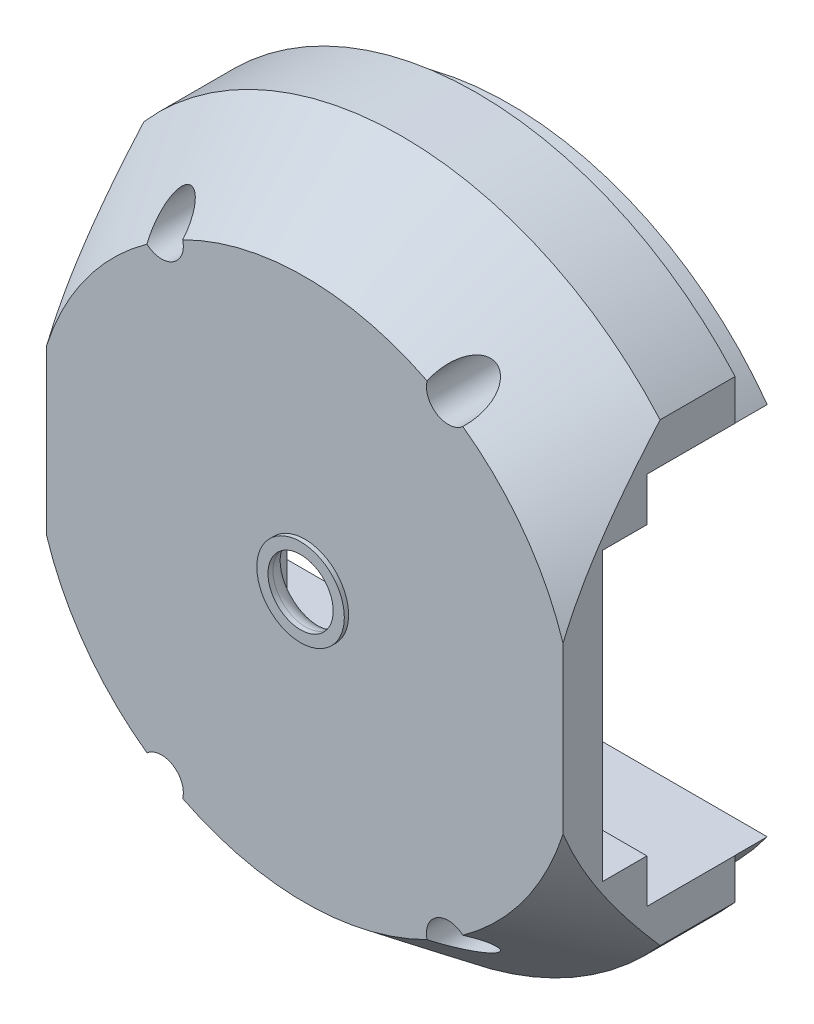
SolidWorks part; units mm, degrees
ref_plane "Front Plane" through (0, 0, 0) normal (0, 0, 1) x (1, 0, 0)
ref_plane "Top Plane" through (0, 0, 0) normal (0, 1, 0) x (1, 0, 0)
ref_plane "Right Plane" through (0, 0, 0) normal (1, 0, 0) x (0, 0, -1)
sketch "Sketch1" plane through (0, 0, 0) normal (0, 0, 1) x (1, 0, 0)
  line L1 (-18.8872, 0) -> (15.5738, 0) construction
  arc A0 (-22.225, -0.0261) -> (22.225, 0) centre (0, 0) ccw
  arc A1 (-22.225, -0.0261) -> (22.225, 0) centre (0, 0) cw
  dimension "D1" = 44.45
extrude "Extrude1" add sketch "Sketch1" along normal blind 2.25
sketch "Sketch2" plane through (0, 0, 2.25) normal (0, 0, 1) x (1, 0, 0)
  line L1 (-19.1115, 0) -> (18.219, 0) construction
  arc A0 (-23.9999, -0.0783) -> (23.9995, 0.1489) centre (0, 0) ccw
  arc A1 (-23.9999, -0.0783) -> (23.9995, 0.1489) centre (0, 0) cw
  dimension "D1" = 48
extrude "Extrude2" add sketch "Sketch2" along normal blind 12
chamfer "Chamfer1" distance 5.1 angle 53 1 edges at (-24, 0, 14.25)
sketch "Sketch6" plane through (0, 0, 0) normal (0, 0, -1) x (-1, 0, 0)
  line L0 (-30, 13.05) -> (30, 13.05)
  line L1 (-30, -13.05) -> (30, -13.05)
  line L2 (-30, -13.05) -> (-30, 13.05)
  line L3 (-30, 0) -> (30, 0) construction
  line L4 (30, -13.05) -> (30, 13.05)
  dimension "D2" = 30
  dimension "D3" = 30
  dimension "D1" = 13.05
extrude "Cut-Extrude1" cut sketch "Sketch6" against normal blind 8.4
sketch "Sketch9" plane through (0, 0, 0) normal (0, 0, -1) x (-1, 0, 0)
  line L1 (-28, -20) -> (-18, -20)
  line L2 (-28, -20) -> (-28, 20)
  line L3 (-28, 20) -> (-18, 20)
  line L4 (-18, -20) -> (-18, 20)
  line L5 (0, 0) -> (0, -27.3159) construction
  line L6 (18, -20) -> (18, 20)
  line L7 (28, 20) -> (18, 20)
  line L8 (28, -20) -> (28, 20)
  line L9 (28, -20) -> (18, -20)
  line L10 (0, 0) -> (18, 0) construction
  dimension "D1" = 40
  dimension "D2" = 18
  dimension "D3" = 10
extrude "Cut-Extrude3" cut sketch "Sketch9" against normal through all
sketch "Sketch10" plane through (0, 0, 8.4) normal (0, 0, -1) x (-1, 0, 0)
  line L1 (22, 10) -> (-22, 10)
  line L2 (22, 10) -> (22, -10)
  line L3 (22, -10) -> (-22, -10)
  line L4 (-22, 10) -> (-22, -10)
  dimension "D1" = 10
  dimension "D2" = 10
  dimension "D3" = 22
  dimension "D4" = 22
extrude "Cut-Extrude4" cut sketch "Sketch10" against normal blind 3.1
sketch "Sketch11" plane through (0, 0, 14.25) normal (0, 0, 1) x (1, 0, 0)
  circle A0 centre (0, 0) radius 6
  dimension "D1" = 12
extrude "Extrude3" [suppressed] add sketch "Sketch11" along normal blind 4.8
sketch "Sketch12" [suppressed] plane through (0, 0, 19.05) normal (0, 0, 1) x (1, 0, 0)
  circle A0 centre (0, 0) radius 2.275
  dimension "D1" = 4.55
extrude "Cut-Extrude5" [suppressed] cut sketch "Sketch12" against normal through all
chamfer "Chamfer2" [suppressed] distance 4 angle 45
sketch "Sketch13" [suppressed] plane through (0, 0, 14.25) normal (0, 0, 1) x (1, 0, 0)
  line L0 (0, 0) -> (0, 33.8431) construction
  line L1 (0, 0) -> (21.9948, 0) construction
  circle A0 centre (10, 16.5) radius 2.5
  circle A1 centre (-10, 16.5) radius 2.5
  circle A2 centre (-10, -16.5) radius 2.5
  circle A3 centre (10, -16.5) radius 2.5
  dimension "D3" = 5
  dimension "D1" = 10
  dimension "D2" = 16.5
extrude "Cut-Extrude6" [suppressed] cut sketch "Sketch13" against normal blind 5
sketch "Sketch14" [suppressed] plane through (0, 0, 9.25) normal (0, 0, 1) x (1, 0, 0)
  line L0 (0, 0) -> (16.3574, 0) construction
  line L1 (0, 0) -> (0, 20.9629) construction
  circle A0 centre (10, 16.5) radius 1.15
  circle A1 centre (-10, 16.5) radius 1.15
  circle A2 centre (-10, -16.5) radius 1.15
  circle A3 centre (10, -16.5) radius 1.15
  dimension "D1" = 2.3
extrude "Cut-Extrude7" [suppressed] cut sketch "Sketch14" against normal through all
sketch "Sketch15" plane through (0, 0, 0) normal (0, 0, -1) x (-1, 0, 0)
  line L0 (0, 0) -> (22.4929, 0) construction
  line L1 (0, 0) -> (0, 30.0852) construction
  line L2 (4, -13) -> (4, 13)
  line L3 (-4, -13) -> (-4, 13)
  line L4 (0, 0) -> (-14.6849, 0) construction
  arc A0 (4, 13) -> (-4, 13) centre (0, 13) ccw
  arc A1 (4, -13) -> (-4, -13) centre (0, -13) cw
  point P3 (-4, 0)
  point P13 (4, 0)
  dimension "D1" = 13
  dimension "D2" = 4
extrude "Cut-Extrude8" cut sketch "Sketch15" against normal blind 13
sketch "Sketch16" plane through (0, 0, 0) normal (0, 0, -1) x (-1, 0, 0)
  line L0 (0, 0) -> (-26.9468, 0) construction
  line L1 (0, 0) -> (0, -31.7311) construction
  circle A0 centre (-10, -16.5) radius 1.525
  circle A1 centre (10, -16.5) radius 1.525
  circle A2 centre (10, 16.5) radius 1.525
  circle A3 centre (-10, 16.5) radius 1.525
  dimension "D1" = 3.05
  dimension "D2" = 16.5
  dimension "D3" = 10
extrude "Cut-Extrude9" cut sketch "Sketch16" against normal through all
sketch "Sketch17" plane through (0, 0, 14.25) normal (0, 0, 1) x (1, 0, 0)
  circle A0 centre (0, 0) radius 2.275
  dimension "D1" = 4.55
extrude "Cut-Extrude10" cut sketch "Sketch17" against normal through all
sketch "Sketch18" plane through (0, 0, 14.25) normal (0, 0, 1) x (1, 0, 0)
  circle A0 centre (0, 0) radius 2.275 construction
  circle A1 centre (0, 0) radius 2.275
  circle A2 centre (0, 0) radius 3.05
  dimension "D1" = 6.1
extrude "Extrude4" add sketch "Sketch18" along normal blind 0.3
chamfer "Chamfer3" [suppressed] distance 0.7 angle 45
fillet "Fillet1" radius 1.2 1 edges at (-2.275, 0, 13)
sketch "Sketch19" plane through (0, 0, 13) normal (0, 0, -1) x (-1, 0, 0)
  line L1 (4, 7) -> (-4, 7)
  line L2 (4, -7) -> (-4, -7)
  line L3 (-4, 13) -> (-4, -13)
  line L4 (4, -13) -> (4, 13)
  line L6 (0, 0) -> (13.3401, 0) construction
  line L7 (-4, 13) -> (-4, 7)
  line L8 (4, -13) -> (4, -7)
  line L9 (4, 7) -> (4, 13)
  line L10 (-4, -7) -> (-4, -13)
  arc A3 (4, 13) -> (-4, 13) centre (0, 13) ccw
  arc A4 (-4, -13) -> (4, -13) centre (0, -13) ccw
  arc A5 (4, 13) -> (-4, 13) centre (0, 13) ccw
  arc A6 (-4, -13) -> (4, -13) centre (0, -13) ccw
  dimension "D1" = 0
  dimension "D2" = 7
extrude "Cut-Extrude11" [suppressed] cut sketch "Sketch19" against normal through all
sketch "Sketch20" plane through (0, 0, 8.4) normal (0, 0, -1) x (-1, 0, 0)
  line L0 (18, 13.05) -> (3.9997, 13.05) construction
  line L1 (6, 13.05) -> (-6, 13.05)
  line L2 (6, 13.05) -> (6, 10)
  line L3 (6, 10) -> (-6, 10)
  line L4 (-6, 13.05) -> (-6, 10)
  line L5 (-4, 10) -> (-18, 10) construction
  line L6 (4, 13) -> (4, 10) construction
  line L7 (-4, 10) -> (-4, 13) construction
  line L8 (0, 0) -> (10.0865, 0) construction
  line L9 (-6, -13.05) -> (-6, -10)
  line L10 (6, -10) -> (-6, -10)
  line L11 (6, -13.05) -> (6, -10)
  line L12 (6, -13.05) -> (-6, -13.05)
  dimension "D1" = 2
  dimension "D2" = 2
extrude "Extrude8" [suppressed] add sketch "Sketch20" against normal blind 3.1
